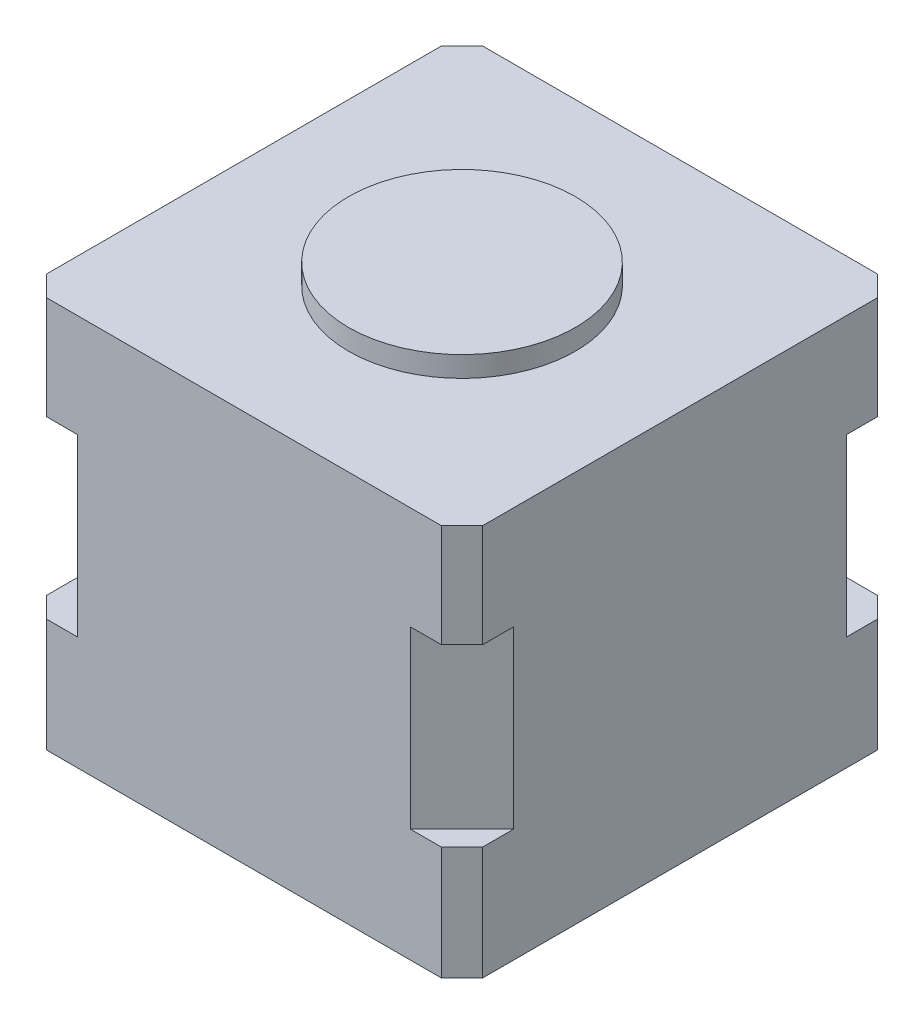
SolidWorks part; units mm, degrees
ref_plane "Front Plane" through (0, 0, 0) normal (0, 0, 1) x (1, 0, 0)
ref_plane "Top Plane" through (0, 0, 0) normal (0, 1, 0) x (1, 0, 0)
ref_plane "Right Plane" through (0, 0, 0) normal (1, 0, 0) x (0, 0, -1)
sketch "Sketch1" plane through (0, 0, 0) normal (0, 1, 0) x (1, 0, 0)
  line L0 (19.15, -21.15) -> (21.15, -19.15)
  line L1 (-19.15, 21.15) -> (19.15, 21.15)
  line L2 (-21.15, 19.15) -> (-21.15, -19.15)
  line L3 (-19.15, -21.15) -> (19.15, -21.15)
  line L4 (21.15, 19.15) -> (21.15, -19.15)
  line L5 (-21.15, 21.15) -> (21.15, -21.15) construction
  line L6 (-21.15, -21.15) -> (21.15, 21.15) construction
  line L7 (-21.15, -19.15) -> (-19.15, -21.15)
  line L8 (-21.15, 19.15) -> (-19.15, 21.15)
  line L9 (19.15, 21.15) -> (21.15, 19.15)
  point P0 (0, 0)
  dimension "D1" = 42.3
  dimension "D2" = 42.3
  dimension "D3" = 2
  dimension "D4" = 45
  dimension "D5" = 2
  dimension "D6" = 45
  dimension "D7" = 2
  dimension "D8" = 45
  dimension "D9" = 2
  dimension "D10" = 45
extrude "Boss-Extrude1" add sketch "Sketch1" along normal blind 11
sketch "Sketch2" plane through (0, 11, 0) normal (0, 1, 0) x (1, 0, 0)
  line L0 (16.15, -21.15) -> (21.15, -16.15)
  line L1 (-16.15, 21.15) -> (16.15, 21.15)
  line L2 (-21.15, 16.15) -> (-21.15, -16.15)
  line L3 (-16.15, -21.15) -> (16.15, -21.15)
  line L4 (21.15, 16.15) -> (21.15, -16.15)
  line L5 (-21.15, 21.15) -> (21.15, -21.15) construction
  line L6 (-21.15, -21.15) -> (21.15, 21.15) construction
  line L7 (-21.15, -16.15) -> (-16.15, -21.15)
  line L8 (16.15, 21.15) -> (21.15, 16.15)
  line L9 (-21.15, 16.15) -> (-16.15, 21.15)
  point P0 (0, 0)
  dimension "D1" = 42.3
  dimension "D2" = 42.3
extrude "Boss-Extrude2" add sketch "Sketch2" along normal blind 17
sketch "Sketch3" plane through (0, 28, 0) normal (0, 1, 0) x (1, 0, 0)
  line L0 (19.15, -21.15) -> (21.15, -19.15)
  line L1 (-19.15, 21.15) -> (19.15, 21.15)
  line L2 (-21.15, 19.15) -> (-21.15, -19.15)
  line L3 (-19.15, -21.15) -> (19.15, -21.15)
  line L4 (21.15, 19.15) -> (21.15, -19.15)
  line L5 (-21.15, 21.15) -> (21.15, -21.15) construction
  line L6 (-21.15, -21.15) -> (21.15, 21.15) construction
  line L7 (19.15, 21.15) -> (21.15, 19.15)
  line L8 (-21.15, 19.15) -> (-19.15, 21.15)
  line L9 (-21.15, -19.15) -> (-19.15, -21.15)
  point P0 (0, 0)
  dimension "D1" = 42.3
  dimension "D2" = 42.3
extrude "Boss-Extrude3" add sketch "Sketch3" along normal blind 10
sketch "Sketch4" plane through (0, 38, 0) normal (0, 1, 0) x (1, 0, 0)
  circle A0 centre (0, 0) radius 11
  dimension "D1" = 22
extrude "Boss-Extrude4" add sketch "Sketch4" along normal blind 2
sketch "Sketch8" plane through (0, 0, 0) normal (0, -1, 0) x (1, 0, 0)
  line L0 (-30.0282, 0) -> (31.49, 0) construction
  line L1 (0, 25.3918) -> (0, -26.839) construction
  circle A0 centre (-15.5, 15.5) radius 1.5
  circle A1 centre (15.5, 15.5) radius 1.5
  circle A2 centre (15.5, -15.5) radius 1.5
  circle A3 centre (-15.5, -15.5) radius 1.5
  dimension "D1" = 3
  dimension "D2" = 31
  dimension "D3" = 31
extrude "Cut-Extrude2" cut sketch "Sketch8" against normal blind 4.5
